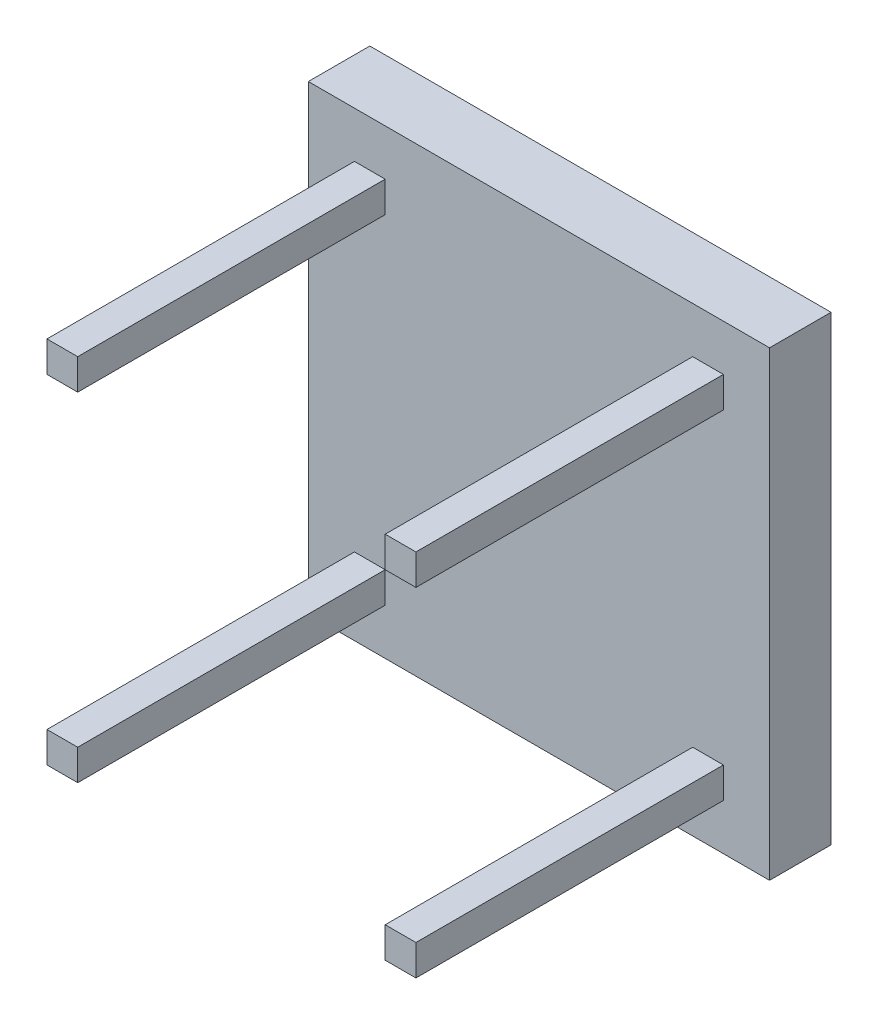
SolidWorks part; units mm, degrees
other "Markup1"
sketch "Sketch3" plane through (150, 150, 240) normal (0.0076, 0.025, 0.9997) x (0.0091, 0.9996, -0.025)
ref_plane "Front Plane" through (0, 0, 0) normal (0, 0, 1) x (1, 0, 0)
ref_plane "Top Plane" through (0, 0, 0) normal (0, 1, 0) x (1, 0, 0)
ref_plane "Right Plane" through (0, 0, 0) normal (1, 0, 0) x (0, 0, -1)
sketch "Sketch1" plane through (0, 0, 0) normal (0, 0, 1) x (1, 0, 0)
  line L0 (150, 0) -> (-150, 0) construction
  line L1 (-150, -150) -> (-150, 150)
  line L2 (-150, 150) -> (150, 150)
  line L3 (150, 150) -> (150, -150)
  line L4 (150, -150) -> (-150, -150)
  point P4 (0, 0)
  point P8 (-150, 0)
  dimension "D1" = 300
  dimension "D2" = 300
extrude "Boss-Extrude1" add sketch "Sketch1" along normal blind 40
sketch "Sketch2" plane through (0, 0, 40) normal (0, 0, 1) x (1, 0, 0)
  line L0 (0, 150) -> (0, -150) construction
  line L1 (-150, 150) -> (-150, -150) construction
  line L2 (-120, 120) -> (-120, 100)
  line L3 (-120, 100) -> (-100, 100)
  line L4 (-100, 100) -> (-100, 120)
  line L5 (-100, 120) -> (-120, 120)
  line L6 (-120, 120) -> (-150, 120)
  line L7 (-150, 120) -> (-150, 150)
  line L8 (150, 150) -> (-150, 150) construction
  line L9 (-150, -150) -> (150, -150) construction
  line L10 (120, 100) -> (100, 100)
  line L11 (100, 100) -> (100, 120)
  line L12 (100, 120) -> (120, 120)
  line L13 (120, 120) -> (120, 100)
  line L14 (-150, 0) -> (150, 0) construction
  line L15 (150, -150) -> (150, 150) construction
  line L16 (120, -100) -> (100, -100)
  line L17 (120, -120) -> (120, -100)
  line L18 (100, -120) -> (120, -120)
  line L19 (100, -100) -> (100, -120)
  line L20 (-100, -100) -> (-100, -120)
  line L21 (-100, -120) -> (-120, -120)
  line L22 (-120, -120) -> (-120, -100)
  line L23 (-120, -100) -> (-100, -100)
  dimension "D1" = 20
  dimension "D2" = 20
  dimension "D3" = 30
  dimension "D4" = 30
extrude "Boss-Extrude2" add sketch "Sketch2" along normal blind 200 contours L13 L12 L11 L10 | L4 L5 L2 L3 | L23 L22 L21 L20 | L16 L19 L18 L17
